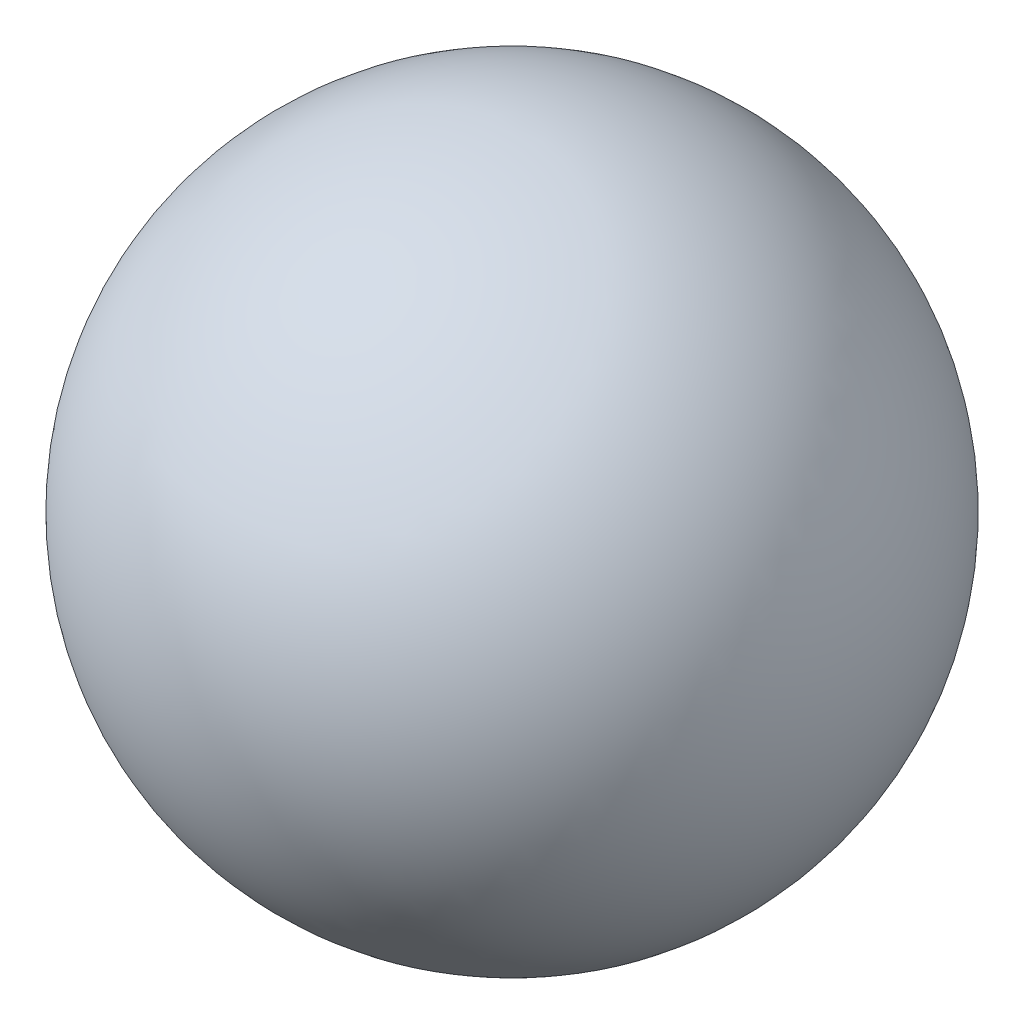
SolidWorks part; units mm, degrees
ref_plane "前基準面" through (0, 0, 0) normal (0, 0, 1) x (1, 0, 0)
ref_plane "上基準面" through (0, 0, 0) normal (0, 1, 0) x (1, 0, 0)
ref_plane "右基準面" through (0, 0, 0) normal (1, 0, 0) x (0, 0, -1)
ref_plane "平面1"
sketch "草圖1" plane through (0, 0, 0) normal (0, 0, 1) x (1, 0, 0)
  line L0 (0, 0) -> (0, 30)
  line L1 (0, -30) -> (0, 0)
  line L2 (0, 0) -> (0, -30) construction
  arc A0 (0, -30) -> (0, 30) centre (0, 0) ccw
  dimension "D1" = 60
revolve "迴轉1" add sketch "草圖1" angle 360 about L2
